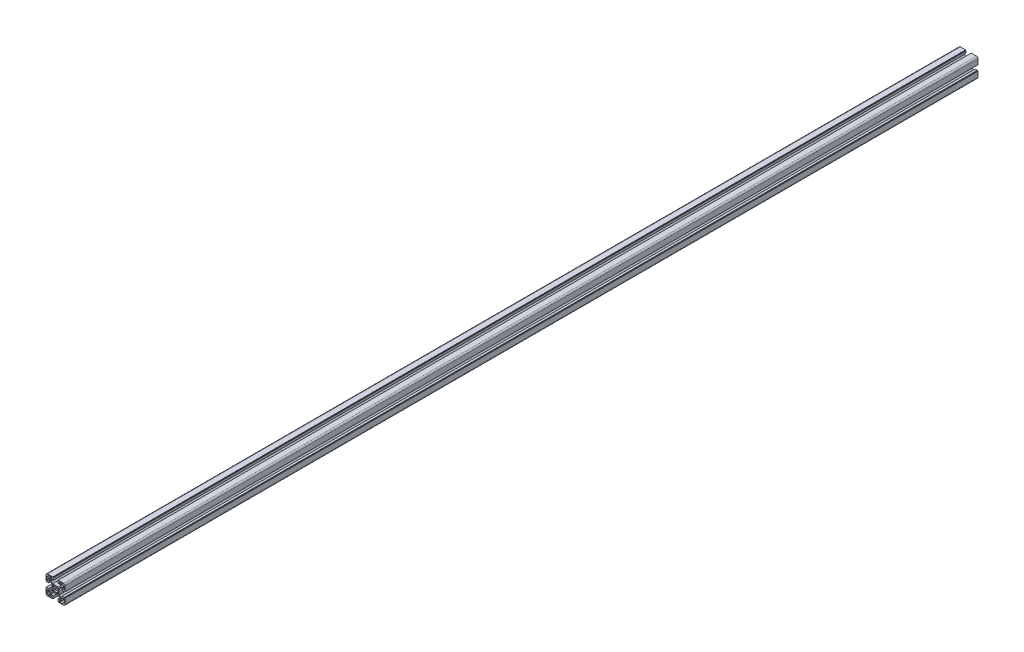
SolidWorks part; units mm, degrees
material "6061 Alloy"
ref_plane "Front Plane" through (0, 0, 0) normal (0, 0, 1) x (1, 0, 0)
ref_plane "Top Plane" through (0, 0, 0) normal (0, 1, 0) x (1, 0, 0)
ref_plane "Right Plane" through (0, 0, 0) normal (1, 0, 0) x (0, 0, -1)
sketch "Sketch1" plane through (0, 0, 0) normal (0, 0, 1) x (1, 0, 0)
  line L0 (5.8, -20) -> (17, -20)
  line L1 (14, -10.05) -> (11.4642, -10.05)
  line L2 (0, -21.1722) -> (0, 18.817) construction
  line L3 (0, 21.1722) -> (0, -18.817) construction
  line L4 (14.5, -18.5) -> (9.5, -18.5)
  line L5 (18.5, 5) -> (14, 5)
  line L6 (6.0858, -7.5) -> (10.05, -11.4642)
  line L7 (20, 5.8) -> (18.5, 5.8)
  line L8 (14, 5) -> (14, 10.05)
  line L9 (18.5, 5.8) -> (18.5, 5)
  line L10 (18.5, 14.5) -> (17.25, 14.5)
  line L11 (14.5, 11.75) -> (15.5, 11.75)
  line L12 (14.5, 17.25) -> (14.5, 18.5)
  line L13 (18.5, 9.5) -> (18.5, 14.5)
  line L14 (15.5, 11.75) -> (15.5, 9.5)
  line L15 (20, 17) -> (20, 5.8)
  line L16 (5.5, 5.5) -> (2.3979, 5.5)
  line L17 (2.3979, 5.5) -> (1.9983, 4.5833)
  line L18 (5.5, 2.3979) -> (5.5, 5.5)
  line L19 (4.5833, 1.9983) -> (5.5, 2.3979)
  line L20 (5, -14) -> (5, -18.5)
  line L21 (11.4642, 10.05) -> (7.5, 6.0858)
  line L22 (-6.0858, 7.5) -> (6.0858, 7.5)
  line L23 (11.75, 15.5) -> (11.75, 14.5)
  line L24 (5, -18.5) -> (5.8, -18.5)
  line L25 (5.8, -18.5) -> (5.8, -20)
  line L26 (10.05, -11.4642) -> (10.05, -14)
  line L27 (10.05, -14) -> (5, -14)
  line L28 (9.5, -15.5) -> (11.75, -15.5)
  line L29 (11.75, -15.5) -> (11.75, -14.5)
  line L30 (9.5, 15.5) -> (11.75, 15.5)
  line L31 (10.05, 14) -> (5, 14)
  line L32 (10.05, 11.4642) -> (10.05, 14)
  line L33 (5.8, 18.5) -> (5.8, 20)
  line L34 (5, 18.5) -> (5.8, 18.5)
  line L35 (7.5, -6.0858) -> (7.5, 6.0858)
  line L36 (5, 14) -> (5, 18.5)
  line L37 (6.0858, 7.5) -> (10.05, 11.4642)
  line L38 (14.5, 18.5) -> (9.5, 18.5)
  line L39 (14, 10.05) -> (11.4642, 10.05)
  line L40 (5.8, 20) -> (17, 20)
  line L41 (-18.5, -5) -> (-14, -5)
  line L42 (-6.0858, -7.5) -> (6.0858, -7.5)
  line L43 (11.4642, -10.05) -> (7.5, -6.0858)
  line L44 (-20, -5.8) -> (-18.5, -5.8)
  line L45 (-14, -5) -> (-14, -10.05)
  line L46 (-18.5, -5.8) -> (-18.5, -5)
  line L47 (-18.5, -14.5) -> (-17.25, -14.5)
  line L48 (4.5833, -1.9983) -> (5.5, -2.3979)
  line L49 (5.5, -2.3979) -> (5.5, -5.5)
  line L50 (2.3979, -5.5) -> (1.9983, -4.5833)
  line L51 (5.5, -5.5) -> (2.3979, -5.5)
  line L52 (-14.5, -11.75) -> (-15.5, -11.75)
  line L53 (-14.5, -17.25) -> (-14.5, -18.5)
  line L54 (-18.5, -9.5) -> (-18.5, -14.5)
  line L55 (-15.5, -11.75) -> (-15.5, -9.5)
  line L56 (-20, -17) -> (-20, -5.8)
  line L57 (-5.5, -5.5) -> (-2.3979, -5.5)
  line L58 (-2.3979, -5.5) -> (-1.9983, -4.5833)
  line L59 (-5.5, -2.3979) -> (-5.5, -5.5)
  line L60 (-4.5833, -1.9983) -> (-5.5, -2.3979)
  line L61 (-11.4642, -10.05) -> (-7.5, -6.0858)
  line L62 (-5.8, 20) -> (-17, 20)
  line L63 (-14, 10.05) -> (-11.4642, 10.05)
  line L64 (-14.5, 18.5) -> (-9.5, 18.5)
  line L65 (-6.0858, 7.5) -> (-10.05, 11.4642)
  line L66 (-5, 14) -> (-5, 18.5)
  line L67 (-7.5, -6.0858) -> (-7.5, 6.0858)
  line L68 (-5, 18.5) -> (-5.8, 18.5)
  line L69 (-5.8, 18.5) -> (-5.8, 20)
  line L70 (-10.05, 11.4642) -> (-10.05, 14)
  line L71 (-10.05, 14) -> (-5, 14)
  line L72 (-9.5, 15.5) -> (-11.75, 15.5)
  line L73 (-11.75, -15.5) -> (-11.75, -14.5)
  line L74 (-9.5, -15.5) -> (-11.75, -15.5)
  line L75 (-10.05, -14) -> (-5, -14)
  line L76 (-10.05, -11.4642) -> (-10.05, -14)
  line L77 (-5.8, -18.5) -> (-5.8, -20)
  line L78 (-5, -18.5) -> (-5.8, -18.5)
  line L79 (-11.75, 15.5) -> (-11.75, 14.5)
  line L80 (-11.4642, 10.05) -> (-7.5, 6.0858)
  line L81 (-5, -14) -> (-5, -18.5)
  line L82 (-4.5833, 1.9983) -> (-5.5, 2.3979)
  line L83 (-5.5, 2.3979) -> (-5.5, 5.5)
  line L84 (-2.3979, 5.5) -> (-1.9983, 4.5833)
  line L85 (-5.5, 5.5) -> (-2.3979, 5.5)
  line L86 (-20, 17) -> (-20, 5.8)
  line L87 (-15.5, 11.75) -> (-15.5, 9.5)
  line L88 (20, -17) -> (20, -5.8)
  line L89 (15.5, -11.75) -> (15.5, -9.5)
  line L90 (18.5, -9.5) -> (18.5, -14.5)
  line L91 (14.5, -17.25) -> (14.5, -18.5)
  line L92 (14.5, -11.75) -> (15.5, -11.75)
  line L93 (18.5, -14.5) -> (17.25, -14.5)
  line L94 (-18.5, 9.5) -> (-18.5, 14.5)
  line L95 (-14.5, 17.25) -> (-14.5, 18.5)
  line L96 (18.5, -5.8) -> (18.5, -5)
  line L97 (14, -5) -> (14, -10.05)
  line L98 (20, -5.8) -> (18.5, -5.8)
  line L99 (18.5, -5) -> (14, -5)
  line L100 (-14.5, 11.75) -> (-15.5, 11.75)
  line L101 (-18.5, 14.5) -> (-17.25, 14.5)
  line L102 (-18.5, 5.8) -> (-18.5, 5)
  line L103 (-14, 5) -> (-14, 10.05)
  line L104 (-20, 5.8) -> (-18.5, 5.8)
  line L105 (-6.0858, -7.5) -> (-10.05, -11.4642)
  line L106 (-18.5, 5) -> (-14, 5)
  line L107 (-14.5, -18.5) -> (-9.5, -18.5)
  line L108 (-20, 0) -> (20.788, 0) construction
  line L109 (-14, -10.05) -> (-11.4642, -10.05)
  line L110 (-5.8, -20) -> (-17, -20)
  arc A0 (14.5, -11.75) -> (11.75, -14.5) centre (14.5, -14.5) ccw
  arc A1 (18.5, 9.5) -> (15.5, 9.5) centre (17, 9.5) cw
  arc A2 (14.5, 17.25) -> (17.25, 14.5) centre (14.5, 14.5) cw
  arc A3 (17, 20) -> (20, 17) centre (17, 17) cw
  arc A4 (-1.9983, 4.5833) -> (1.9983, 4.5833) centre (0, 0) cw
  arc A5 (9.5, 15.5) -> (9.5, 18.5) centre (9.5, 17) cw
  arc A6 (9.5, -15.5) -> (9.5, -18.5) centre (9.5, -17) ccw
  arc A7 (14.5, 11.75) -> (11.75, 14.5) centre (14.5, 14.5) cw
  arc A8 (4.5833, -1.9983) -> (4.5833, 1.9983) centre (0, 0) ccw
  arc A9 (-18.5, -9.5) -> (-15.5, -9.5) centre (-17, -9.5) cw
  arc A10 (-14.5, -17.25) -> (-17.25, -14.5) centre (-14.5, -14.5) cw
  arc A11 (-1.9983, -4.5833) -> (1.9983, -4.5833) centre (0, 0) ccw
  arc A12 (-17, -20) -> (-20, -17) centre (-17, -17) cw
  arc A13 (-4.5833, -1.9983) -> (-4.5833, 1.9983) centre (0, 0) cw
  arc A14 (-14.5, 11.75) -> (-11.75, 14.5) centre (-14.5, 14.5) ccw
  arc A15 (-9.5, -15.5) -> (-9.5, -18.5) centre (-9.5, -17) cw
  arc A16 (-9.5, 15.5) -> (-9.5, 18.5) centre (-9.5, 17) ccw
  arc A17 (-17, 20) -> (-20, 17) centre (-17, 17) ccw
  arc A18 (17, -20) -> (20, -17) centre (17, -17) ccw
  arc A19 (14.5, -17.25) -> (17.25, -14.5) centre (14.5, -14.5) ccw
  arc A20 (18.5, -9.5) -> (15.5, -9.5) centre (17, -9.5) ccw
  arc A21 (-14.5, 17.25) -> (-17.25, 14.5) centre (-14.5, 14.5) ccw
  arc A22 (-18.5, 9.5) -> (-15.5, 9.5) centre (-17, 9.5) ccw
  arc A23 (-14.5, -11.75) -> (-11.75, -14.5) centre (-14.5, -14.5) cw
  point P55 (7.5, 0)
  point P101 (-7.5, 0)
  point P116 (0, -7.5)
  point P149 (0, 7.5)
extrude "Extrude1" add sketch "Sketch1" along normal blind 1920
hole_wizard "M12 Tapped Hole1" [suppressed] positions "3DSketch2" profile "Sketch3" tap size "M12" standard "ISO"
sketch3d "3DSketch2"
  line L0 (-20, 17, 0) -> (-20, 5.8, 0) construction
  line L1 (-5.8, 20, 0) -> (-17, 20, 0) construction
  line L2 (-5.8, 20, 200) -> (-17, 20, 200) construction
  line L3 (-20, 17, 200) -> (-20, 5.8, 200) construction
  point P0 (0, 0, 200)
  point P2 (0, 0, 0)
  dimension "D1" = 20
  dimension "D2" = 20
  dimension "D3" = 20
  dimension "D4" = 20
sketch "Sketch3" plane through (0, 0, 200) normal (1, 0, 0) x (0, -1, 0)
  line L0 (0, 0) -> (0, 35.8144)
  line L1 (0, 35.8144) -> (5.1, 32.75)
  line L2 (5.1, 32.75) -> (5.1, 0.925)
  line L3 (5.1, 0.925) -> (6.025, 0)
  line L5 (6.025, 0) -> (0, 0)
  line L6 (-5.1, 0.925) -> (-6.025, 0) construction
  line L10 (0, 35.8144) -> (-5.1, 32.75) construction
  line L11 (0, -6.35) -> (0, 107.95) construction
  dimension "Tap Drill Dia." = 10.2
  dimension "Tap Drill Depth" = 32.75
  dimension "Near C'Sink Dia." = 12.05
  dimension "Near C'Sink Angle" = 90
  dimension "Drill Angle" = 118
cosmetic thread "Hole Thread1" [suppressed] parameters "D1"=24, "D2"=12
cosmetic thread "Filettatura del foro1" [suppressed] parameters "D1"=24, "D2"=12
hole_wizard "Ø9.8 (9.8) Diameter Hole1" [suppressed] positions "3DSketch3" profile "Sketch4" hole size "Ø9.8" standard "ISO"
sketch3d "3DSketch3"
  line L0 (-5.8, 20, 200) -> (-17, 20, 200) construction
  line L1 (20, -17, 200) -> (20, -5.8, 200) construction
  line L2 (17, 20, 0) -> (5.8, 20, 0) construction
  line L3 (20, -17, 0) -> (20, -5.8, 0) construction
  point P0 (0, 20, 184)
  point P2 (20, 0, 184)
  point P4 (0, 20, 16)
  point P6 (20, 0, 16)
  dimension "D1" = 16
  dimension "D2" = 20
  dimension "D3" = 20
  dimension "D4" = 16
  dimension "D5" = 16
  dimension "D6" = 16
sketch "Sketch4" plane through (0, 20, 184) normal (1, 0, 0) x (0, 0, 1)
  line L0 (0, 0) -> (0, 40)
  line L1 (0, 40) -> (4.9, 40)
  line L2 (4.9, 40) -> (4.9, 0)
  line L5 (4.9, 0) -> (0, 0)
  line L11 (0, -6.35) -> (0, 107.95) construction
  dimension "Thru Hole Dia." = 9.8
  dimension "Thru Hole Depth" = 40
hole_wizard "Ø17.0 (17) Diameter Hole1" [suppressed] positions "3DSketch4" profile "Sketch5" hole size "Ø17.0" standard "ISO"
sketch3d "3DSketch4"
  line L0 (-5.8, 20, 200) -> (-17, 20, 200) construction
  line L1 (-5.8, 20, 0) -> (-17, 20, 0) construction
  point P0 (0, 20, 177.5)
  point P2 (0, 20, 22.5)
  dimension "D1" = 20
  dimension "D2" = 22.5
  dimension "D3" = 22.5
sketch "Sketch5" plane through (0, 20, 177.5) normal (1, 0, 0) x (0, 0, 1)
  line L0 (0, 0) -> (0, 40)
  line L1 (0, 40) -> (8.5, 40)
  line L2 (8.5, 40) -> (8.5, 0)
  line L5 (8.5, 0) -> (0, 0)
  line L11 (0, -6.35) -> (0, 107.95) construction
  dimension "Thru Hole Dia." = 17
  dimension "Thru Hole Depth" = 40
